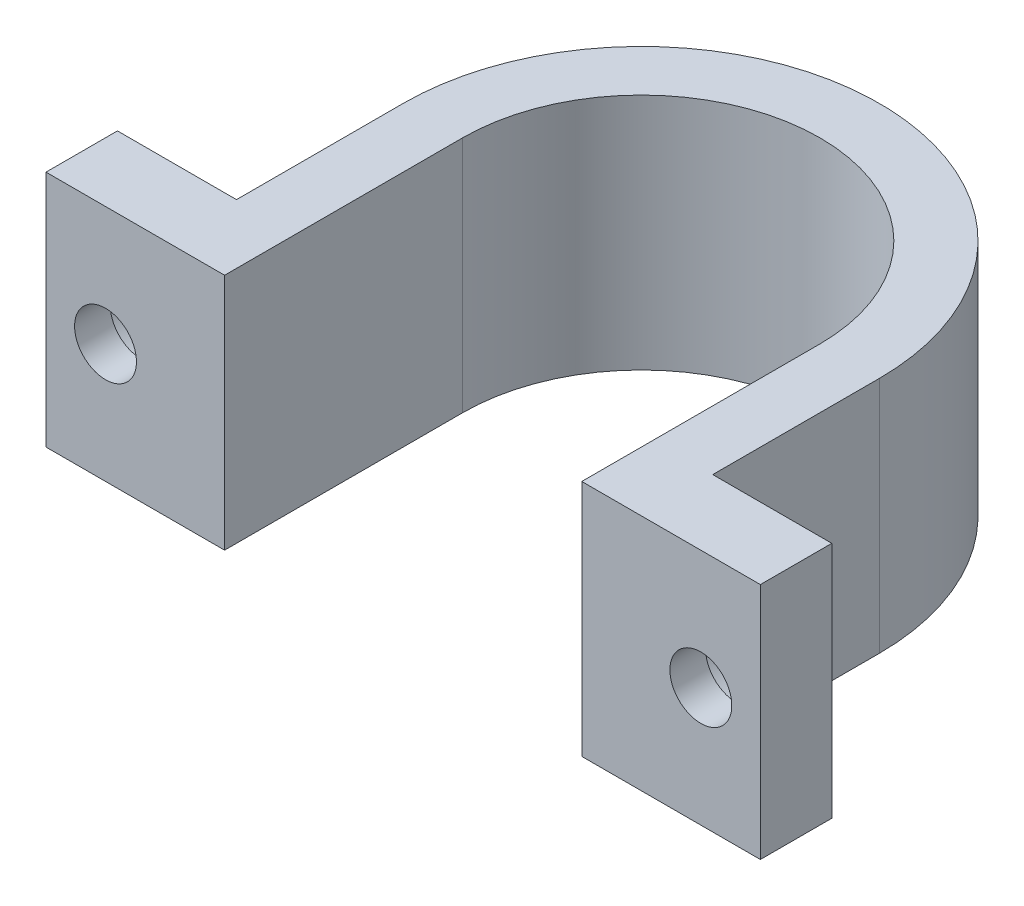
SolidWorks part; units mm, degrees
ref_plane "前视基准面" through (0, 0, 0) normal (0, 0, 1) x (1, 0, 0)
ref_plane "上视基准面" through (0, 0, 0) normal (0, 1, 0) x (1, 0, 0)
ref_plane "右视基准面" through (0, 0, 0) normal (1, 0, 0) x (0, 0, -1)
other "Configuration Table"
sketch "草图1" plane through (0, 0, 0) normal (0, 1, 0) x (1, 0, 0)
  line L0 (15, 0) -> (20, 0)
  line L1 (-15, 0) -> (-20, 0)
  line L2 (-15, 20) -> (-15, 0)
  line L4 (15, 20) -> (15, 0)
  line L8 (-20, 0) -> (-30, 0)
  line L13 (-30, 0) -> (-30, 6)
  line L14 (-30, 6) -> (-20, 6)
  line L15 (-20, 6) -> (-20, 20)
  line L17 (20, 0) -> (30, 0)
  line L18 (30, 0) -> (30, 6)
  line L21 (30, 6) -> (20, 6)
  line L22 (20, 6) -> (20, 20)
  arc A2 (-15, 20) -> (15, 20) centre (0, 20) cw
  arc A3 (-20, 20) -> (20, 20) centre (0, 20) cw
extrude "凸台-拉伸1" add sketch "草图1" along normal blind 20
sketch "草图3" plane through (0, 0, -6) normal (0, 0, -1) x (-1, 0, 0)
  line L0 (20, 20) -> (30, 0)
  line L1 (-30, 20) -> (-20, 0)
  circle A0 centre (-25, 10) radius 2.6
  circle A1 centre (25, 10) radius 2.6
extrude "切除-拉伸1" cut sketch "草图3" against normal blind 20 contours L0 A1 | L0 A1 | L1 A0 | L1 A0
sketch "草图4" plane through (0, 0, -6) normal (0, 0, -1) x (-1, 0, 0)
  circle A0 centre (-25, 10) radius 4.9
  circle A1 centre (25, 10) radius 4.9
extrude "切除-拉伸3" cut sketch "草图4" against normal blind 3
